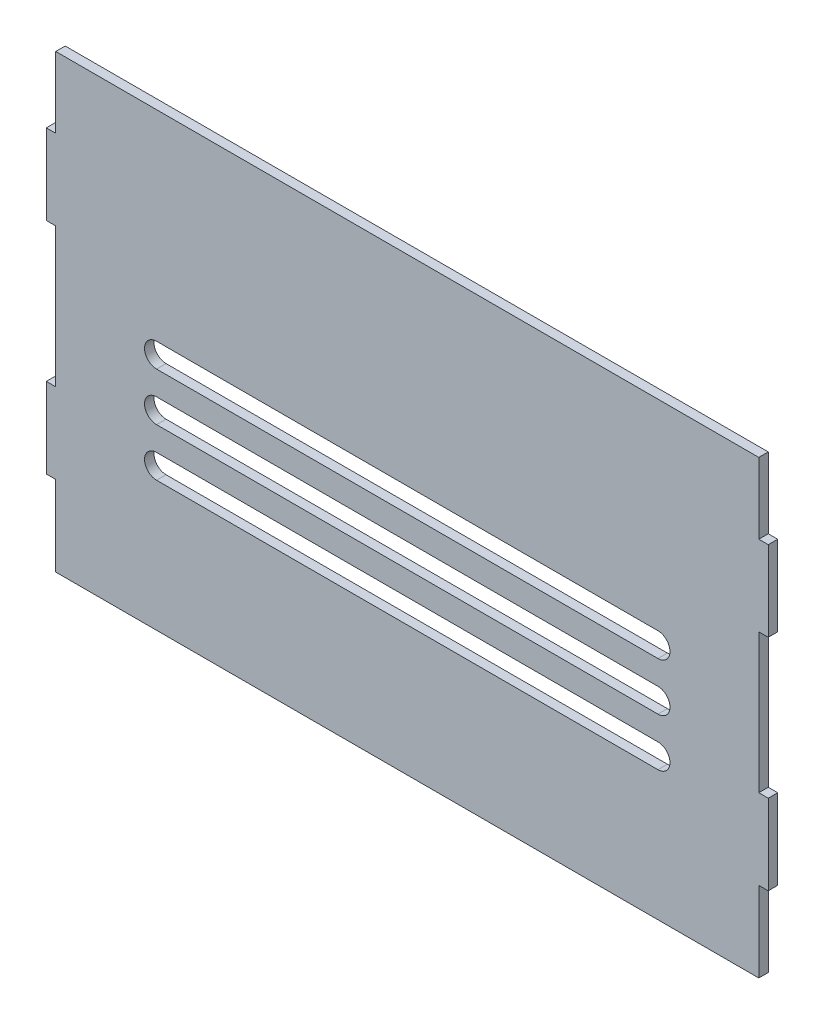
SolidWorks part; units mm, degrees
ref_plane "Front Plane" through (0, 0, 0) normal (0, 0, 1) x (1, 0, 0)
ref_plane "Top Plane" through (0, 0, 0) normal (0, 1, 0) x (1, 0, 0)
ref_plane "Right Plane" through (0, 0, 0) normal (1, 0, 0) x (0, 0, -1)
sketch "Sketch1" plane through (0, 0, 0) normal (0, 0, 1) x (1, 0, 0)
  line L0 (-77.3818, 72.847) -> (-77.3818, 55.177)
  line L1 (-77.3818, 72.847) -> (97.8938, 72.847)
  line L3 (-77.3818, -39.563) -> (97.8938, -39.563)
  line L5 (-77.3818, 55.177) -> (-79.744, 55.177)
  line L6 (-79.744, 55.177) -> (-79.744, 35.177)
  line L7 (-79.744, 35.177) -> (-77.3818, 35.177)
  line L8 (-77.3818, 35.177) -> (-77.3818, 0.437)
  line L9 (-77.3818, 0.437) -> (-79.744, 0.437)
  line L10 (-79.744, 0.437) -> (-79.744, -19.563)
  line L11 (-79.744, -19.563) -> (-77.3818, -19.563)
  line L12 (-77.3818, -19.563) -> (-77.3818, -39.563)
  line L13 (97.8938, 72.847) -> (97.8938, 55.177)
  line L14 (97.8938, 55.177) -> (100.256, 55.177)
  line L15 (100.256, 55.177) -> (100.256, 35.177)
  line L16 (100.256, 35.177) -> (97.8938, 35.177)
  line L17 (97.8938, 35.177) -> (97.8938, 0.437)
  line L18 (97.8938, 0.437) -> (100.256, 0.437)
  line L19 (100.256, 0.437) -> (100.256, -19.563)
  line L20 (100.256, -19.563) -> (97.8938, -19.563)
  line L21 (97.8938, -19.563) -> (97.8938, -39.563)
  dimension "D1" = 112.41
  dimension "D2" = 2.3622
  dimension "D3" = 2.3622
  dimension "D4" = 2.3622
  dimension "D5" = 2.3622
  dimension "D6" = 2.3622
  dimension "D7" = 2.3622
  dimension "D8" = 2.3622
  dimension "D9" = 2.3622
  dimension "D10" = 20
  dimension "D11" = 20
  dimension "D12" = 34.74
  dimension "D13" = 20
  dimension "D14" = 20
  dimension "D15" = 20
  dimension "D16" = 34.74
  dimension "D17" = 20
  dimension "D18" = 180
extrude "Boss-Extrude1" add sketch "Sketch1" along normal blind 2.3622
sketch "Sketch2" plane through (0, 0, 2.3622) normal (0, 0, 1) x (1, 0, 0)
  line L0 (-52.244, 19.847) -> (72.756, 19.847) construction
  line L1 (-52.244, 22.847) -> (72.756, 22.847)
  line L2 (-52.244, 16.847) -> (72.756, 16.847)
  line L3 (97.8938, 72.847) -> (-77.3818, 72.847) construction
  line L4 (-52.244, 7.847) -> (72.756, 7.847) construction
  line L5 (-52.244, 10.847) -> (72.756, 10.847)
  line L6 (-52.244, 4.847) -> (72.756, 4.847)
  line L7 (-52.244, -4.153) -> (72.756, -4.153) construction
  line L8 (-52.244, -1.153) -> (72.756, -1.153)
  line L9 (-52.244, -7.153) -> (72.756, -7.153)
  line L26 (-52.244, -16.153) -> (72.756, -16.153) construction
  line L27 (-52.244, -13.153) -> (72.756, -13.153)
  line L28 (-52.244, -19.153) -> (72.756, -19.153)
  line L29 (-52.244, -28.153) -> (72.756, -28.153) construction
  line L30 (-52.244, -25.153) -> (72.756, -25.153)
  line L31 (-52.244, -31.153) -> (72.756, -31.153)
  line L32 (-52.244, -40.153) -> (72.756, -40.153) construction
  line L33 (-52.244, -37.153) -> (72.756, -37.153)
  line L34 (-52.244, -43.153) -> (72.756, -43.153)
  line L35 (-52.244, -16.153) -> (72.756, -16.153) construction
  line L36 (-52.244, -13.153) -> (72.756, -13.153)
  line L37 (-52.244, -19.153) -> (72.756, -19.153)
  line L38 (-52.244, -28.153) -> (72.756, -28.153) construction
  line L39 (-52.244, -25.153) -> (72.756, -25.153)
  line L40 (-52.244, -31.153) -> (72.756, -31.153)
  line L41 (-52.244, -40.153) -> (72.756, -40.153) construction
  line L42 (-52.244, -37.153) -> (72.756, -37.153)
  line L43 (-52.244, -43.153) -> (72.756, -43.153)
  arc A0 (-52.244, 22.847) -> (-52.244, 16.847) centre (-52.244, 19.847) ccw
  arc A1 (72.756, 16.847) -> (72.756, 22.847) centre (72.756, 19.847) ccw
  arc A2 (-52.244, 10.847) -> (-52.244, 4.847) centre (-52.244, 7.847) ccw
  arc A3 (72.756, 4.847) -> (72.756, 10.847) centre (72.756, 7.847) ccw
  arc A4 (-52.244, -1.153) -> (-52.244, -7.153) centre (-52.244, -4.153) ccw
  arc A5 (72.756, -7.153) -> (72.756, -1.153) centre (72.756, -4.153) ccw
  arc A24 (-52.244, -13.153) -> (-52.244, -19.153) centre (-52.244, -16.153) ccw
  arc A25 (72.756, -19.153) -> (72.756, -13.153) centre (72.756, -16.153) ccw
  arc A26 (-52.244, -25.153) -> (-52.244, -31.153) centre (-52.244, -28.153) ccw
  arc A27 (72.756, -31.153) -> (72.756, -25.153) centre (72.756, -28.153) ccw
  arc A28 (-52.244, -37.153) -> (-52.244, -43.153) centre (-52.244, -40.153) ccw
  arc A29 (72.756, -43.153) -> (72.756, -37.153) centre (72.756, -40.153) ccw
  point P2 (10.256, 19.847)
  point P9 (10.256, 72.847)
  point P13 (10.256, 7.847)
  point P20 (10.256, -4.153)
  point P34 (10.256, -16.153)
  point P41 (10.256, -28.153)
  point P47 (10.256, -40.153)
  point P54 (10.256, -16.153)
  point P61 (10.256, -28.153)
  point P68 (10.256, -40.153)
  point P75 (10.256, -16.153)
  point P82 (10.256, -28.153)
  point P89 (10.256, -40.153)
  dimension "D1" = 3
  dimension "D2" = 125
  dimension "D4" = 50
  dimension "D3" = 6
extrude "Cut-Extrude1" cut sketch "Sketch2" against normal through all
